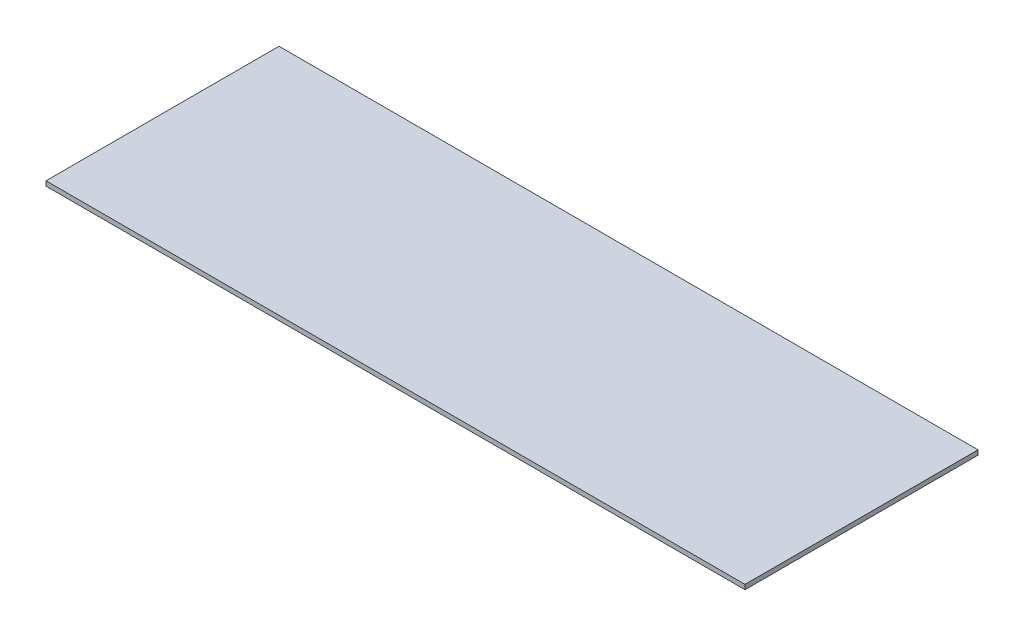
SolidWorks part; units mm, degrees
ref_plane "Front Plane" through (0, 0, 0) normal (0, 0, 1) x (1, 0, 0)
ref_plane "Top Plane" through (0, 0, 0) normal (0, 1, 0) x (1, 0, 0)
ref_plane "Right Plane" through (0, 0, 0) normal (1, 0, 0) x (0, 0, -1)
sketch "Sketch1" plane through (0, 0, 0) normal (0, 1, 0) x (1, 0, 0)
  line L1 (-15, 5) -> (15, 5)
  line L2 (-15, 5) -> (-15, -5)
  line L3 (-15, -5) -> (15, -5)
  line L4 (15, 5) -> (15, -5)
  line L5 (-15, 5) -> (15, -5) construction
  line L6 (-15, -5) -> (15, 5) construction
  point P0 (0, 0)
  dimension "D1" = 30
  dimension "D2" = 10
extrude "Boss-Extrude1" add sketch "Sketch1" along normal blind 0.2
